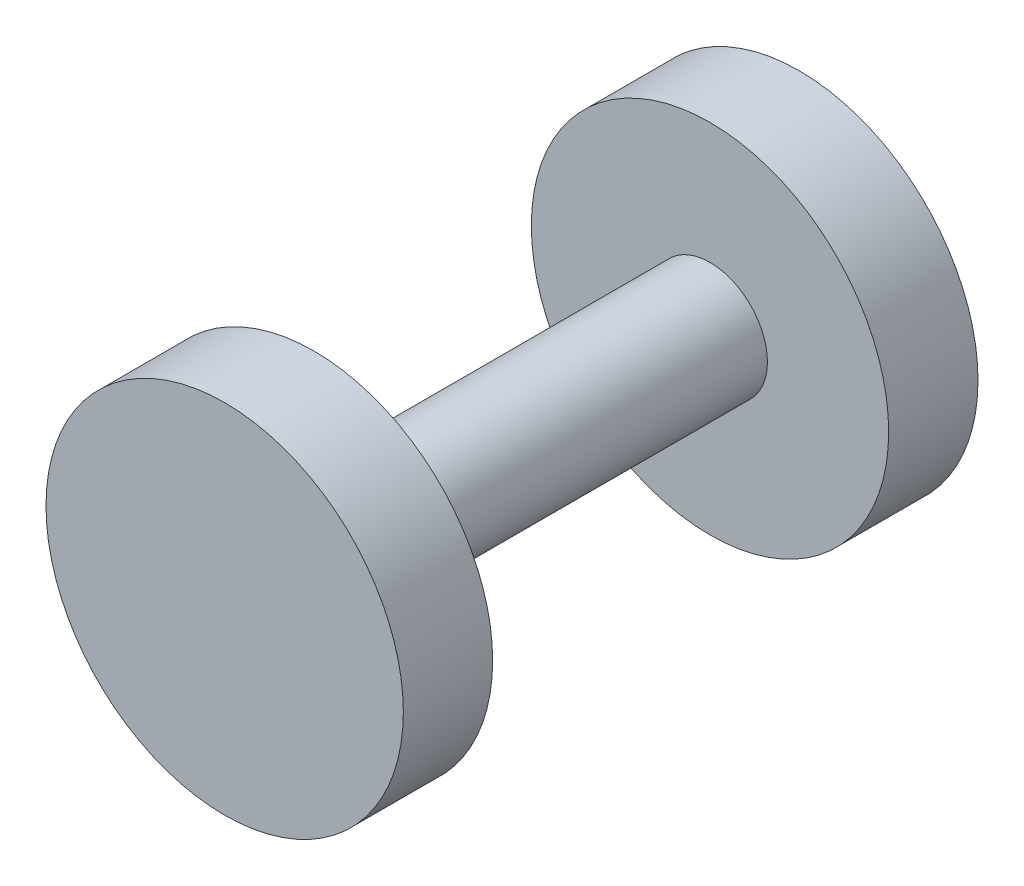
SolidWorks part; units mm, degrees
ref_plane "Front Plane" through (0, 0, 0) normal (0, 0, 1) x (1, 0, 0)
ref_plane "Top Plane" through (0, 0, 0) normal (0, 1, 0) x (1, 0, 0)
ref_plane "Right Plane" through (0, 0, 0) normal (1, 0, 0) x (0, 0, -1)
sketch "Sketch2" plane through (0, 0, 0) normal (1, 0, 0) x (0, 0, -1)
  line L0 (7.3285, 0) -> (-24.8375, 0)
  line L1 (-24.8375, 0) -> (-24.8375, 10)
  line L2 (-24.8375, 10) -> (-19.8375, 10)
  line L3 (-19.8375, 10) -> (-19.8375, 3.213)
  line L4 (-19.8375, 3.213) -> (2.3285, 3.213)
  line L5 (2.3285, 3.213) -> (2.3285, 10)
  line L6 (2.3285, 10) -> (7.3285, 10)
  line L7 (7.3285, 10) -> (7.3285, 0)
  dimension "D1" = 10
  dimension "D2" = 5
revolve "Revolve1" add sketch "Sketch2" angle 360 about L0
